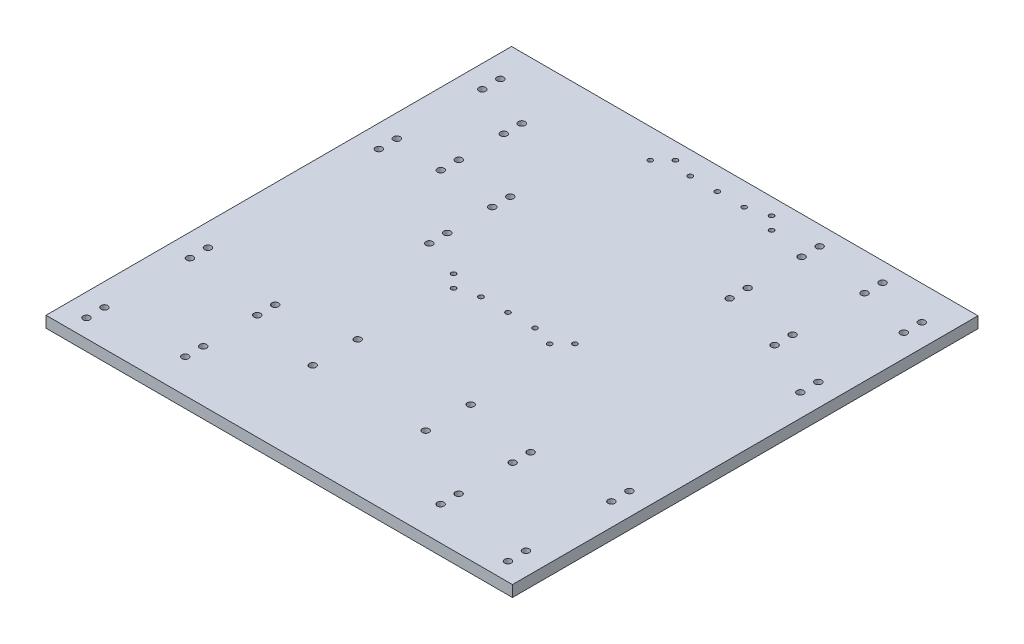
SolidWorks part; units mm, degrees
ref_plane "Front Plane" through (0, 0, 0) normal (0, 0, 1) x (1, 0, 0)
ref_plane "Top Plane" through (0, 0, 0) normal (0, 1, 0) x (1, 0, 0)
ref_plane "Right Plane" through (0, 0, 0) normal (1, 0, 0) x (0, 0, -1)
sketch "Sketch1" plane through (0, 0, 0) normal (0, 1, 0) x (1, 0, 0)
  line L1 (131.7003, -127) -> (-131.7003, -127)
  line L2 (131.7003, -127) -> (131.7003, 127)
  line L3 (131.7003, 127) -> (-131.7003, 127)
  line L4 (-131.7003, -127) -> (-131.7003, 127)
  line L5 (131.7003, -127) -> (-131.7003, 127) construction
  line L6 (131.7003, 127) -> (-131.7003, -127) construction
  point P0 (0, 0)
  dimension "D1" = 263.4005
  dimension "D2" = 254
extrude "Boss-Extrude1" add sketch "Sketch1" along normal blind 6.35
hole_wizard "#6 Clearance Hole1" positions "Sketch3" profile "Sketch4" hole size "#6" standard "ANSI Inch" end condition through all
sketch "Sketch3" plane through (0, 6.35, 0) normal (0, 1, 0) x (1, 0, 0)
  line L0 (131.7003, 127) -> (-131.7003, 127) construction
  line L1 (119.0003, 116.84) -> (119.0003, 106.68)
  line L3 (119.0003, 58.42) -> (119.0003, 48.26)
  line L5 (131.7003, -127) -> (131.7003, 127) construction
  point P0 (119.0003, 116.84)
  point P2 (119.0003, 106.68)
  point P4 (119.0003, 58.42)
  point P6 (119.0003, 48.26)
  dimension "D1" = 10.16
  dimension "D2" = 10.16
  dimension "D3" = 48.26
  dimension "D4" = 12.7
  dimension "D5" = 12.7
  dimension "D6" = 10.16
sketch "Sketch4" plane through (119.0003, 6.35, -116.84) normal (1, 0, 0) x (0, 0, 1)
  line L0 (0, 0) -> (0, 6.35)
  line L1 (0, 6.35) -> (1.8986, 6.35)
  line L2 (1.8986, 6.35) -> (1.8986, 0)
  line L5 (1.8986, 0) -> (0, 0)
  line L11 (0, -6.35) -> (0, 107.95) construction
  dimension "Thru Hole Dia." = 3.7973
  dimension "Thru Hole Depth" = 6.35
ref_plane "Plane1" through (0, 0, 0) normal (0, 0, -1) x (-1, 0, 0)
mirror "Mirror1" about plane through (0, 0, 0) normal (0, 0, -1) of "#6 Clearance Hole1"
hole_wizard "#6 Clearance Hole2" positions "Sketch5" profile "Sketch6" hole size "#6" standard "ANSI Inch" end condition through all
sketch "Sketch5" plane through (0, 6.35, 0) normal (0, 1, 0) x (1, 0, 0)
  line L0 (88.6193, 125.062) -> (88.6193, 114.902)
  line L2 (88.6193, 74.262) -> (88.6193, 64.102)
  line L4 (131.7003, -127) -> (131.7003, 127) construction
  line L5 (131.7003, 127) -> (-131.7003, 127) construction
  point P0 (88.6193, 125.062)
  point P2 (88.6193, 114.902)
  point P4 (88.6193, 74.262)
  point P6 (88.6193, 64.102)
  dimension "D1" = 43.0809
  dimension "D2" = 43.0809
  dimension "D3" = 10.16
  dimension "D4" = 10.16
  dimension "D5" = 1.938
  dimension "D6" = 40.64
sketch "Sketch6" plane through (88.6193, 6.35, -125.062) normal (1, 0, 0) x (0, 0, 1)
  line L0 (0, 0) -> (0, 6.35)
  line L1 (0, 6.35) -> (1.8986, 6.35)
  line L2 (1.8986, 6.35) -> (1.8986, 0)
  line L5 (1.8986, 0) -> (0, 0)
  line L11 (0, -6.35) -> (0, 107.95) construction
  dimension "Thru Hole Dia." = 3.7973
  dimension "Thru Hole Depth" = 6.35
hole_wizard "#6 Clearance Hole3" positions "Sketch7" profile "Sketch8" hole size "#6" standard "ANSI Inch" end condition through all
sketch "Sketch7" plane through (0, 6.35, 0) normal (0, 1, 0) x (1, 0, 0)
  line L0 (53.0593, 84.422) -> (53.0593, 74.262)
  line L3 (53.0593, 125.062) -> (53.0593, 114.902)
  circle A0 centre (88.6193, 114.902) radius 1.8986 construction
  circle A1 centre (88.6193, 64.102) radius 1.8986 construction
  circle A3 centre (88.6193, 125.062) radius 1.8986 construction
  point P0 (53.0593, 125.062)
  point P2 (53.0593, 114.902)
  point P4 (53.0593, 84.422)
  point P6 (53.0593, 74.262)
  dimension "D6" = 30.48
  dimension "D1" = 10.16
  dimension "D2" = 10.16
  dimension "D3" = 35.56
  dimension "D4" = 35.56
  dimension "D5" = 0
sketch "Sketch8" plane through (53.0593, 6.35, -125.062) normal (1, 0, 0) x (0, 0, 1)
  line L0 (0, 0) -> (0, 6.35)
  line L1 (0, 6.35) -> (1.8986, 6.35)
  line L2 (1.8986, 6.35) -> (1.8986, 0)
  line L5 (1.8986, 0) -> (0, 0)
  line L11 (0, -6.35) -> (0, 107.95) construction
  dimension "Thru Hole Dia." = 3.7973
  dimension "Thru Hole Depth" = 6.35
hole_wizard "#6 Clearance Hole4" positions "Sketch9" profile "Sketch10" hole size "#6" standard "ANSI Inch" end condition through all
sketch "Sketch9" plane through (0, 6.35, 0) normal (0, 1, 0) x (1, 0, 0)
  line L0 (72.1119, -57.1703) -> (72.1119, -67.3303)
  line L2 (72.1119, -97.8103) -> (72.1119, -107.9703)
  line L4 (131.7003, -127) -> (131.7003, 127) construction
  line L5 (-131.7003, -127) -> (131.7003, -127) construction
  point P0 (72.1119, -57.1703)
  point P2 (72.1119, -67.3303)
  point P4 (72.1119, -97.8103)
  point P6 (72.1119, -107.9703)
  dimension "D1" = 10.16
  dimension "D2" = 10.16
  dimension "D3" = 59.5884
  dimension "D4" = 59.5884
  dimension "D5" = 30.48
  dimension "D6" = 19.0297
sketch "Sketch10" plane through (72.1119, 6.35, 57.1703) normal (1, 0, 0) x (0, 0, 1)
  line L0 (0, 0) -> (0, 6.35)
  line L1 (0, 6.35) -> (1.8986, 6.35)
  line L2 (1.8986, 6.35) -> (1.8986, 0)
  line L5 (1.8986, 0) -> (0, 0)
  line L11 (0, -6.35) -> (0, 107.95) construction
  dimension "Thru Hole Dia." = 3.7973
  dimension "Thru Hole Depth" = 6.35
ref_plane "Plane2" through (0, 0, 0) normal (-1, 0, 0) x (0, 0, 1)
mirror "Mirror2" about plane through (0, 0, 0) normal (-1, 0, 0) of "#6 Clearance Hole4", "#6 Clearance Hole1", "Mirror1"
hole_wizard "#6 Clearance Hole5" positions "Sketch11" profile "Sketch12" hole size "#6" standard "ANSI Inch" end condition through all
sketch "Sketch11" plane through (0, 6.35, 0) normal (0, 1, 0) x (1, 0, 0)
  line L0 (-91.1619, 101.1225) -> (-91.1619, 90.9625)
  line L2 (-91.1619, 65.5625) -> (-91.1619, 55.4025)
  line L4 (131.7003, 127) -> (-131.7003, 127) construction
  line L5 (-131.7003, 127) -> (-131.7003, -127) construction
  point P0 (-91.1619, 101.1225)
  point P2 (-91.1619, 90.9625)
  point P4 (-91.1619, 65.5625)
  point P6 (-91.1619, 55.4025)
  dimension "D1" = 10.16
  dimension "D2" = 10.16
  dimension "D3" = 25.8775
  dimension "D4" = 40.5384
  dimension "D5" = 40.5384
  dimension "D6" = 25.4
sketch "Sketch12" plane through (-91.1619, 6.35, -101.1225) normal (1, 0, 0) x (0, 0, 1)
  line L0 (0, 0) -> (0, 6.35)
  line L1 (0, 6.35) -> (1.8986, 6.35)
  line L2 (1.8986, 6.35) -> (1.8986, 0)
  line L5 (1.8986, 0) -> (0, 0)
  line L11 (0, -6.35) -> (0, 107.95) construction
  dimension "Thru Hole Dia." = 3.7973
  dimension "Thru Hole Depth" = 6.35
hole_wizard "#6 Clearance Hole6" positions "Sketch13" profile "Sketch14" hole size "#6" standard "ANSI Inch" end condition through all
sketch "Sketch13" plane through (0, 6.35, 0) normal (0, 1, 0) x (1, 0, 0)
  line L0 (-58.6169, 62.07) -> (-58.6169, 51.91)
  line L2 (-58.6169, 26.51) -> (-58.6169, 16.35)
  line L4 (-131.7003, 127) -> (-131.7003, -127) construction
  line L5 (131.7003, 127) -> (-131.7003, 127) construction
  point P0 (-58.6169, 62.07)
  point P2 (-58.6169, 51.91)
  point P4 (-58.6169, 26.51)
  point P6 (-58.6169, 16.35)
  dimension "D1" = 10.16
  dimension "D2" = 10.16
  dimension "D3" = 73.0834
  dimension "D4" = 73.0834
  dimension "D5" = 25.4
  dimension "D6" = 64.93
sketch "Sketch14" plane through (-58.6169, 6.35, -62.07) normal (1, 0, 0) x (0, 0, 1)
  line L0 (0, 0) -> (0, 6.35)
  line L1 (0, 6.35) -> (1.8986, 6.35)
  line L2 (1.8986, 6.35) -> (1.8986, 0)
  line L5 (1.8986, 0) -> (0, 0)
  line L11 (0, -6.35) -> (0, 107.95) construction
  dimension "Thru Hole Dia." = 3.7973
  dimension "Thru Hole Depth" = 6.35
hole_wizard "Tap Drill for #6-32 Tap1" positions "Sketch15" profile "Sketch16" hole size "#6-32" standard "ANSI Inch" end condition through all
sketch "Sketch15" plane through (0, 6.35, 0) normal (0, 1, 0) x (1, 0, 0)
  line L2 (-36.9176, 1.2471) -> (-29.8056, 1.2471)
  line L3 (-36.9176, 1.2471) -> (-36.9176, 8.3591)
  line L4 (-36.9176, 8.3591) -> (-29.8056, 8.3591)
  line L5 (-29.8056, 1.2471) -> (-29.8056, 8.3591)
  line L6 (131.7003, 127) -> (-131.7003, 127) construction
  line L7 (-131.7003, 127) -> (-131.7003, -127) construction
  point P0 (-36.9176, 8.3591)
  point P6 (-29.8056, 1.2471)
  dimension "D1" = 94.7826
  dimension "D2" = 7.112
  dimension "D3" = 7.112
  dimension "D4" = 118.6409
sketch "Sketch16" plane through (-36.9176, 6.35, -8.3591) normal (1, 0, 0) x (0, 0, 1)
  line L0 (0, 0) -> (0, 6.35)
  line L1 (0, 6.35) -> (1.3525, 6.35)
  line L2 (1.3525, 6.35) -> (1.3525, 0)
  line L5 (1.3525, 0) -> (0, 0)
  line L11 (0, -6.35) -> (0, 107.95) construction
  dimension "Thru Hole Dia." = 2.7051
  dimension "Thru Hole Depth" = 6.35
hole_wizard "Tap Drill for #6-32 Tap2" positions "Sketch17" profile "Sketch18" hole size "#6-32" standard "ANSI Inch" end condition through all
sketch "Sketch17" plane through (0, 6.35, 0) normal (0, 1, 0) x (1, 0, 0)
  line L1 (-36.9176, 119.4003) -> (-29.8056, 119.4003)
  line L2 (-36.9176, 119.4003) -> (-36.9176, 126.5123)
  line L3 (-36.9176, 126.5123) -> (-29.8056, 126.5123)
  line L4 (-29.8056, 119.4003) -> (-29.8056, 126.5123)
  circle A1 centre (-36.9176, 8.3591) radius 1.3525 construction
  circle A3 centre (-29.8056, 1.2471) radius 1.3525 construction
  point P2 (-29.8056, 126.5123)
  point P4 (-36.9176, 119.4003)
  point P94 (0, 0)
  point P95 (0, 0)
  dimension "D1" = 125.2652
  dimension "D2" = 7.112
  dimension "D3" = 7.112
  dimension "D4" = 0
sketch "Sketch18" plane through (-29.8056, 6.35, -126.5123) normal (1, 0, 0) x (0, 0, 1)
  line L0 (0, 0) -> (0, 6.35)
  line L1 (0, 6.35) -> (1.3525, 6.35)
  line L2 (1.3525, 6.35) -> (1.3525, 0)
  line L5 (1.3525, 0) -> (0, 0)
  line L11 (0, -6.35) -> (0, 107.95) construction
  dimension "Thru Hole Dia." = 2.7051
  dimension "Thru Hole Depth" = 6.35
hole_wizard "Tap Drill for #6-32 Tap3" positions "Sketch19" profile "Sketch20" hole size "#6-32" standard "ANSI Inch" end condition through all
sketch "Sketch19" plane through (0, 6.35, 0) normal (0, 1, 0) x (1, 0, 0)
  line L0 (-17.8903, 122.9563) -> (12.5893, 122.9563)
  line L1 (12.5893, 122.9563) -> (-2.6505, 122.9563)
  line L3 (24.5046, 126.5123) -> (31.6166, 126.5123)
  line L4 (24.5046, 126.5123) -> (24.5046, 119.4003)
  line L5 (24.5046, 119.4003) -> (31.6166, 119.4003)
  line L6 (31.6166, 126.5123) -> (31.6166, 119.4003)
  line L9 (24.5046, 1.2471) -> (31.6166, 1.2471)
  line L10 (24.5046, 1.2471) -> (24.5046, 8.3591)
  line L11 (24.5046, 8.3591) -> (31.6166, 8.3591)
  line L12 (31.6166, 1.2471) -> (31.6166, 8.3591)
  circle A0 centre (-29.8056, 1.2471) radius 1.3525 construction
  circle A1 centre (-29.8056, 126.5123) radius 1.3525 construction
  point P0 (-17.8905, 4.8031)
  point P2 (-2.6505, 4.8031)
  point P4 (12.5895, 4.8031)
  point P10 (-17.8903, 122.9563)
  point P12 (-2.6505, 123.0352)
  point P14 (12.5893, 122.9563)
  point P32 (24.5046, 126.5123)
  point P34 (31.6166, 119.4003)
  point P36 (24.5046, 1.2471)
  point P38 (31.6166, 8.3591)
  dimension "D1" = 27.1551
  dimension "D4" = 3.556
  dimension "D5" = 3.556
  dimension "D2" = 15.24
  dimension "D3" = 15.24
  dimension "D6" = 3.556
  dimension "D7" = 15.24
  dimension "D8" = 15.24
  dimension "D9" = 27.1551
  dimension "D10" = 3.556
  dimension "D11" = 27.1551
  dimension "D12" = 7.112
  dimension "D13" = 7.112
  dimension "D14" = 3.556
  dimension "D15" = 7.112
  dimension "D16" = 7.112
  dimension "D17" = 3.556
  dimension "D18" = 11.9151
sketch "Sketch20" plane through (-17.8905, 6.35, -4.8031) normal (1, 0, 0) x (0, 0, 1)
  line L0 (0, 0) -> (0, 6.35)
  line L1 (0, 6.35) -> (1.3525, 6.35)
  line L2 (1.3525, 6.35) -> (1.3525, 0)
  line L5 (1.3525, 0) -> (0, 0)
  line L11 (0, -6.35) -> (0, 107.95) construction
  dimension "Thru Hole Dia." = 2.7051
  dimension "Thru Hole Depth" = 6.35
hole_wizard "#6 Clearance Hole7" positions "Sketch21" profile "Sketch22" hole size "#6" standard "ANSI Inch" end condition through all
sketch "Sketch21" plane through (0, 6.35, 0) normal (0, 1, 0) x (1, 0, 0)
  line L1 (-31.9215, -50.8) -> (31.9214, -50.8)
  line L2 (-31.9215, -50.8) -> (-31.9214, -76.2)
  line L3 (-31.9214, -76.2) -> (31.9214, -76.2)
  line L4 (31.9214, -50.8) -> (31.9214, -76.2)
  line L5 (-131.7003, -127) -> (131.7003, -127) construction
  line L6 (0, 3.4925) -> (0, -3.4925) construction
  point P0 (-31.9215, -50.8)
  point P2 (-31.9214, -76.2)
  point P4 (31.9214, -76.2)
  point P6 (31.9214, -50.8)
  point P94 (0, -50.8)
  dimension "D1" = 63.8429
  dimension "D2" = 25.4
  dimension "D3" = 50.8
  dimension "D4" = 0
sketch "Sketch22" plane through (-31.9215, 6.35, 50.8) normal (1, 0, 0) x (0, 0, 1)
  line L0 (0, 0) -> (0, 6.35)
  line L1 (0, 6.35) -> (1.8986, 6.35)
  line L2 (1.8986, 6.35) -> (1.8986, 0)
  line L5 (1.8986, 0) -> (0, 0)
  line L11 (0, -6.35) -> (0, 107.95) construction
  dimension "Thru Hole Dia." = 3.7973
  dimension "Thru Hole Depth" = 6.35
sketch "Sketch23" plane through (0, 6.35, 0) normal (0, 1, 0) x (1, 0, 0)
  line L0 (131.7003, 127) -> (25.7662, 127) construction
  line L1 (-131.7003, 127) -> (131.7003, 127)
  line L2 (-131.7003, 127) -> (-131.7003, 135.89)
  line L3 (-131.7003, 135.89) -> (131.7003, 135.89)
  line L4 (131.7003, 127) -> (131.7003, 135.89)
  line L5 (-131.7003, 127) -> (-131.7003, -127) construction
  dimension "D1" = 8.89
extrude "Boss-Extrude2" add sketch "Sketch23" against normal blind 6.35
sketch "Sketch24" plane through (0, 6.35, 0) normal (0, 1, 0) x (1, 0, 0)
  circle A0 centre (-29.8056, 126.5123) radius 1.3525
  circle A1 centre (24.5046, 126.5123) radius 1.3525
extrude "Cut-Extrude1" cut sketch "Sketch24" against normal through all
